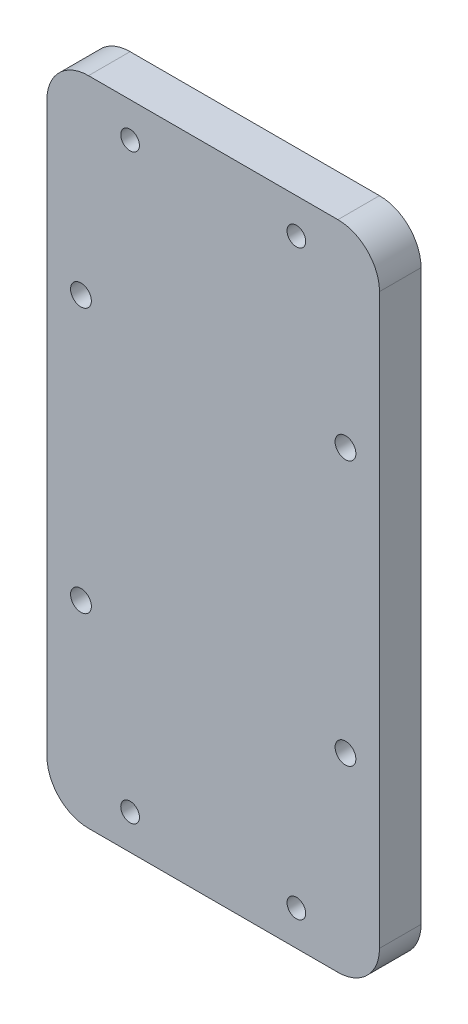
SolidWorks part; units mm, degrees
ref_plane "Front Plane" through (0, 0, 0) normal (1, 0, 0) x (0, 1, 0)
ref_plane "Top Plane" through (0, 0, 0) normal (0, 0, 1) x (0, 1, 0)
ref_plane "Right Plane" through (0, 0, 0) normal (0, 1, 0) x (-1, 0, 0)
sketch "Sketch1" plane through (0, 0, 0) normal (0, 0, 1) x (0, 1, 0)
  line L1 (0, 0) -> (0, 45) construction
  line L2 (0, 0) -> (45, 0) construction
  line L4 (68.4128, 40) -> (-68.4128, 40)
  line L5 (78.4128, 30) -> (78.4128, -30)
  line L6 (68.4128, -40) -> (-68.4128, -40)
  line L7 (-78.4128, 30) -> (-78.4128, -30)
  line L8 (78.4128, 40) -> (-78.4128, -40) construction
  line L9 (78.4128, -40) -> (-78.4128, 40) construction
  circle A6 centre (70, 20) radius 2.25
  circle A7 centre (70, -20) radius 2.25
  circle A8 centre (-70, -20) radius 2.25
  circle A9 centre (-70, 20) radius 2.25
  arc A10 (68.4128, -40) -> (78.4128, -30) centre (68.4128, -30) ccw
  arc A11 (78.4128, 30) -> (68.4128, 40) centre (68.4128, 30) ccw
  arc A12 (-78.4128, 30) -> (-68.4128, 40) centre (-68.4128, 30) cw
  arc A13 (-78.4128, -30) -> (-68.4128, -40) centre (-68.4128, -30) ccw
  dimension "D4" = 4.5
  dimension "D5" = 70
  dimension "D6" = 20
  dimension "D7" = 10
  dimension "D8" = 156.8256
  dimension "D9" = 80
extrude "Boss-Extrude1" add sketch "Sketch1" along normal blind 10
sketch "Sketch2" plane through (0, 0, 10) normal (0, 0, 1) x (1, 0, 0)
  line L0 (0, 0) -> (31.8198, 31.8198) construction
  line L1 (0, 0) -> (-31.8198, 31.8198) construction
  line L2 (0, 0) -> (31.8198, -31.8198) construction
  line L3 (0, 0) -> (-31.8198, -31.8198) construction
  circle A0 centre (0, 0) radius 45 construction
  point P4 (31.8198, 31.8198)
  point P5 (-31.8198, 31.8198)
  point P6 (31.8198, -31.8198)
  point P7 (-31.8198, -31.8198)
  dimension "D1" = 90
hole_wizard "M6 Tapped Hole1" positions "Sketch2" profile "Sketch3" tap size "M6" standard "ISO" end condition through all
sketch "Sketch3" plane through (-31.8198, -31.8198, 10) normal (1, 0, 0) x (0, -1, 0)
  line L0 (0, 0) -> (0, 10)
  line L1 (0, 10) -> (2.5, 10)
  line L2 (2.5, 10) -> (2.5, 0)
  line L5 (2.5, 0) -> (0, 0)
  line L11 (0, -6.35) -> (0, 107.95) construction
  dimension "Thru Tap Drill Dia." = 5
  dimension "Thru Tap Drill Depth" = 10
cosmetic thread "Hole Thread1" parameters "D2"=6
cosmetic thread "Hole Thread2" parameters "D2"=6
cosmetic thread "Hole Thread3" parameters "D2"=6
cosmetic thread "Hole Thread4" parameters "D2"=6
